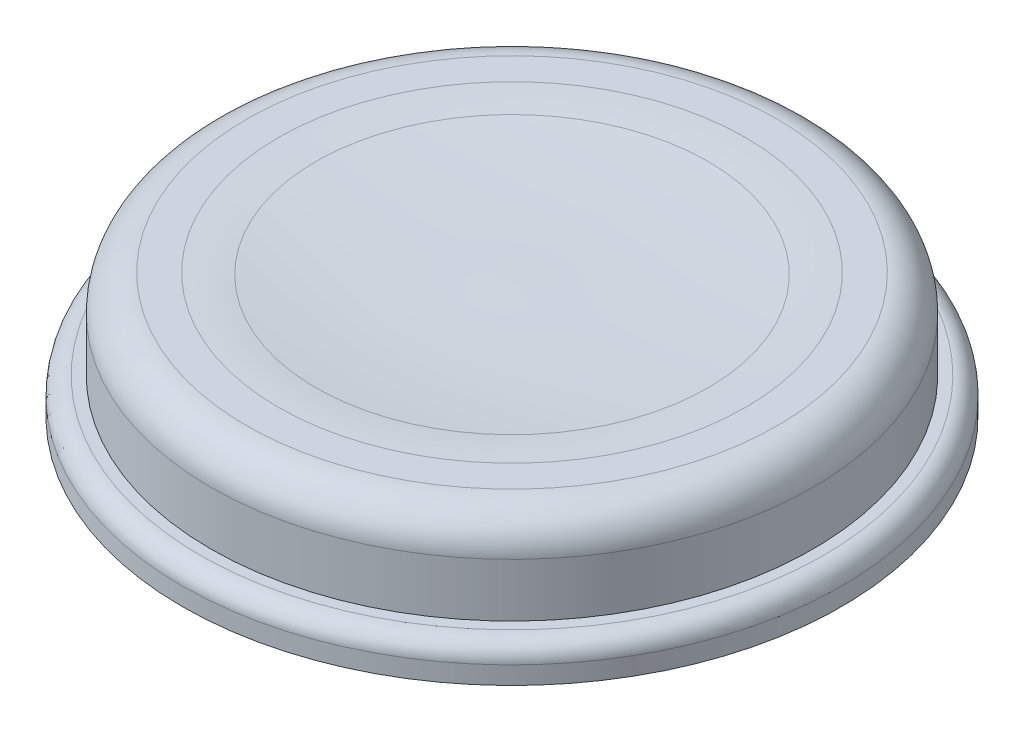
SolidWorks part; units mm, degrees
ref_plane "Front Plane" through (0, 0, 0) normal (0, 0, 1) x (1, 0, 0)
ref_plane "Top Plane" through (0, 0, 0) normal (0, 1, 0) x (1, 0, 0)
ref_plane "Right Plane" through (0, 0, 0) normal (1, 0, 0) x (0, 0, -1)
sketch "Sketch1" plane through (0, 0, 0) normal (0, 1, 0) x (1, 0, 0)
  circle A0 centre (0, 0) radius 15.5
  circle A2 centre (0, 0) radius 16.9
  circle A3 centre (0, 0) radius 19
  circle A4 centre (0, 0) radius 17.5 construction
  dimension "D1" = 31
  dimension "D3" = 38
  dimension "D2" = 33.8
  dimension "D4" = 35
sketch "Sketch2" plane through (0, 0, 0) normal (1, 0, 0) x (0, 0, -1)
  line L0 (19, 0) -> (-19, 0) construction
  line L1 (-17.5, 0) -> (-16.9, 0)
  line L2 (-18.5, -1) -> (-18.5, -2)
  line L3 (-18.5, -2) -> (-14.5, -2)
  line L4 (-14.5, -1) -> (-14.5, -2)
  line L5 (0, 0) -> (0, 8.3313) construction
  line L6 (-13.5, 0) -> (0, 0)
  line L7 (-16.9, 0) -> (-16.9, 3)
  line L10 (-14.9, 5) -> (-13.1156, 5)
  line L11 (0, 0) -> (0, 4.5)
  arc A0 (-16.9, 3) -> (-14.9, 5) centre (-14.9, 3) cw
  arc A1 (-13.5, 0) -> (-14.5, -1) centre (-13.5, -1) ccw
  arc A2 (-17.5, 0) -> (-18.5, -1) centre (-17.5, -1) ccw
  arc A3 (-11.0066, 4.8938) -> (0, 4.5) centre (-2.4702, 89.4641) ccw
  arc A4 (-13.1156, 5) -> (-11.0066, 4.8938) centre (-13.1156, -16) cw
  point P14 (-16.9, 4)
  point P19 (-18.5, 0)
  point P20 (14.9, 4)
  point P25 (-12, 5)
  dimension "D7" = 2
  dimension "D8" = 1
  dimension "D9" = 85
  dimension "D10" = 3
  dimension "D11" = 85
  dimension "D12" = 4.5
  dimension "D13" = 21
  dimension "D1" = 2
  dimension "D2" = 18.5
  dimension "D3" = 4
  dimension "D4" = 12
  dimension "D5" = 16.9
  dimension "D6" = 2.9
revolve "Revolve1" add sketch "Sketch2" angle 360 about L5
sketch "Sketch3" plane through (0, 0, 0) normal (0, -1, 0) x (1, 0, 0)
  circle A0 centre (0, 0) radius 4
  dimension "D1" = 8
extrude "Boss-Extrude3" add sketch "Sketch3" along normal blind 3.6
fillet "Fillet1" radius 1 1 edges at (0, -3.6, -4)
